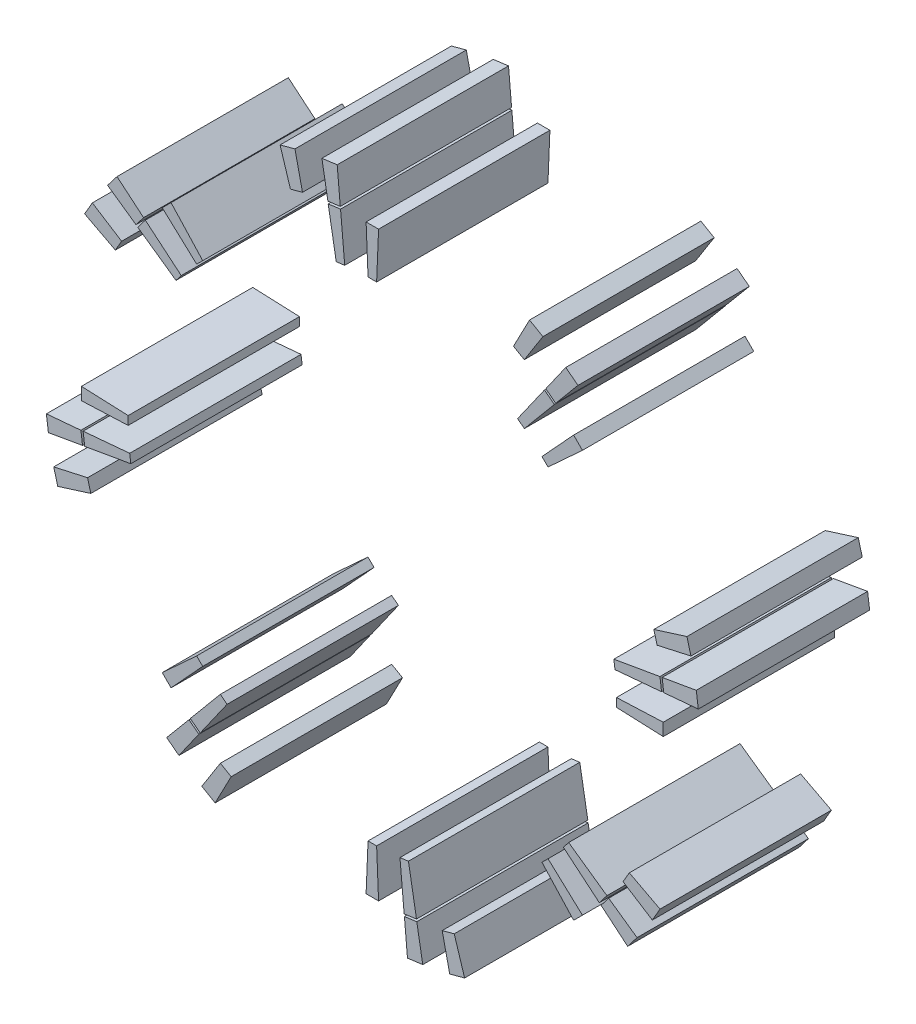
SolidWorks part; units mm, degrees
ref_plane "Спереди" through (0, 0, 0) normal (0, 0, 1) x (1, 0, 0)
ref_plane "Сверху" through (0, 0, 0) normal (0, 1, 0) x (1, 0, 0)
ref_plane "Справа" through (0, 0, 0) normal (1, 0, 0) x (0, 0, -1)
sketch "Эскиз1" plane through (0, 0, 0) normal (0, 0, 1) x (1, 0, 0)
  line L0 (42.755, -0.75) -> (50.9385, -1.0918)
  line L1 (50.9385, -1.0918) -> (50.9385, 1.0918)
  line L2 (50.9385, 1.0918) -> (42.755, 0.75)
  line L3 (42.755, 0.75) -> (42.755, -0.75)
  line L4 (51.0303, 5.617) -> (57.0775, 6.1527)
  line L5 (57.0775, 6.1527) -> (56.7251, 8.8296)
  line L6 (56.7251, 8.8296) -> (50.7452, 7.782)
  line L7 (50.7452, 7.782) -> (51.0303, 5.617)
  line L8 (42.4871, 4.8371) -> (50.6452, 5.5663)
  line L9 (50.6452, 5.5663) -> (50.3602, 7.7313)
  line L10 (50.3602, 7.7313) -> (42.2913, 6.3242)
  line L11 (42.2913, 6.3242) -> (42.4871, 4.8371)
  line L12 (49.8605, 12.2298) -> (55.7861, 13.5502)
  line L13 (55.7861, 13.5502) -> (55.0873, 16.1582)
  line L14 (55.0873, 16.1582) -> (49.2953, 14.339)
  line L15 (49.2953, 14.339) -> (49.8605, 12.2298)
  line L16 (30.7627, 29.702) -> (36.791, 35.2469)
  line L17 (36.791, 35.2469) -> (35.2469, 36.791)
  line L18 (35.2469, 36.791) -> (29.702, 30.7627)
  line L19 (29.702, 30.7627) -> (30.7627, 29.702)
  line L20 (32.112, 40.0557) -> (36.0093, 44.7106)
  line L21 (36.0093, 44.7106) -> (33.8672, 46.3542)
  line L22 (33.8672, 46.3542) -> (30.3796, 41.385)
  line L23 (30.3796, 41.385) -> (32.112, 40.0557)
  line L24 (26.6226, 33.4632) -> (31.8756, 39.7475)
  line L25 (31.8756, 39.7475) -> (30.1432, 41.0769)
  line L26 (30.1432, 41.0769) -> (25.4326, 34.3764)
  line L27 (25.4326, 34.3764) -> (26.6226, 33.4632)
  line L28 (26.609, 43.9044) -> (29.8653, 49.0282)
  line L29 (29.8653, 49.0282) -> (27.527, 50.3782)
  line L30 (27.527, 50.3782) -> (24.7179, 44.9963)
  line L31 (24.7179, 44.9963) -> (26.609, 43.9044)
  line L32 (0.75, 42.755) -> (1.0918, 50.9385)
  line L33 (1.0918, 50.9385) -> (-1.0918, 50.9385)
  line L34 (-1.0918, 50.9385) -> (-0.75, 42.755)
  line L35 (-0.75, 42.755) -> (0.75, 42.755)
  line L36 (-5.617, 51.0303) -> (-6.1527, 57.0775)
  line L37 (-6.1527, 57.0775) -> (-8.8296, 56.7251)
  line L38 (-8.8296, 56.7251) -> (-7.782, 50.7452)
  line L39 (-7.782, 50.7452) -> (-5.617, 51.0303)
  line L40 (-4.8371, 42.4871) -> (-5.5663, 50.6452)
  line L41 (-5.5663, 50.6452) -> (-7.7313, 50.3602)
  line L42 (-7.7313, 50.3602) -> (-6.3242, 42.2913)
  line L43 (-6.3242, 42.2913) -> (-4.8371, 42.4871)
  line L44 (-12.2298, 49.8605) -> (-13.5502, 55.7861)
  line L45 (-13.5502, 55.7861) -> (-16.1582, 55.0873)
  line L46 (-16.1582, 55.0873) -> (-14.339, 49.2953)
  line L47 (-14.339, 49.2953) -> (-12.2298, 49.8605)
  line L48 (-29.702, 30.7627) -> (-35.2469, 36.791)
  line L49 (-35.2469, 36.791) -> (-36.791, 35.2469)
  line L50 (-36.791, 35.2469) -> (-30.7627, 29.702)
  line L51 (-30.7627, 29.702) -> (-29.702, 30.7627)
  line L52 (-40.0557, 32.112) -> (-44.7106, 36.0093)
  line L53 (-44.7106, 36.0093) -> (-46.3542, 33.8672)
  line L54 (-46.3542, 33.8672) -> (-41.385, 30.3796)
  line L55 (-41.385, 30.3796) -> (-40.0557, 32.112)
  line L56 (-33.4632, 26.6226) -> (-39.7475, 31.8756)
  line L57 (-39.7475, 31.8756) -> (-41.0769, 30.1432)
  line L58 (-41.0769, 30.1432) -> (-34.3764, 25.4326)
  line L59 (-34.3764, 25.4326) -> (-33.4632, 26.6226)
  line L60 (-43.9044, 26.609) -> (-49.0282, 29.8653)
  line L61 (-49.0282, 29.8653) -> (-50.3782, 27.527)
  line L62 (-50.3782, 27.527) -> (-44.9963, 24.7179)
  line L63 (-44.9963, 24.7179) -> (-43.9044, 26.609)
  line L64 (-42.755, 0.75) -> (-50.9385, 1.0918)
  line L65 (-50.9385, 1.0918) -> (-50.9385, -1.0918)
  line L66 (-50.9385, -1.0918) -> (-42.755, -0.75)
  line L67 (-42.755, -0.75) -> (-42.755, 0.75)
  line L68 (-51.0303, -5.617) -> (-57.0775, -6.1527)
  line L69 (-57.0775, -6.1527) -> (-56.7251, -8.8296)
  line L70 (-56.7251, -8.8296) -> (-50.7452, -7.782)
  line L71 (-50.7452, -7.782) -> (-51.0303, -5.617)
  line L72 (-42.4871, -4.8371) -> (-50.6452, -5.5663)
  line L73 (-50.6452, -5.5663) -> (-50.3602, -7.7313)
  line L74 (-50.3602, -7.7313) -> (-42.2913, -6.3242)
  line L75 (-42.2913, -6.3242) -> (-42.4871, -4.8371)
  line L76 (-49.8605, -12.2298) -> (-55.7861, -13.5502)
  line L77 (-55.7861, -13.5502) -> (-55.0873, -16.1582)
  line L78 (-55.0873, -16.1582) -> (-49.2953, -14.339)
  line L79 (-49.2953, -14.339) -> (-49.8605, -12.2298)
  line L80 (-30.7627, -29.702) -> (-36.791, -35.2469)
  line L81 (-36.791, -35.2469) -> (-35.2469, -36.791)
  line L82 (-35.2469, -36.791) -> (-29.702, -30.7627)
  line L83 (-29.702, -30.7627) -> (-30.7627, -29.702)
  line L84 (-32.112, -40.0557) -> (-36.0093, -44.7106)
  line L85 (-36.0093, -44.7106) -> (-33.8672, -46.3542)
  line L86 (-33.8672, -46.3542) -> (-30.3796, -41.385)
  line L87 (-30.3796, -41.385) -> (-32.112, -40.0557)
  line L88 (-26.6226, -33.4632) -> (-31.8756, -39.7475)
  line L89 (-31.8756, -39.7475) -> (-30.1432, -41.0769)
  line L90 (-30.1432, -41.0769) -> (-25.4326, -34.3764)
  line L91 (-25.4326, -34.3764) -> (-26.6226, -33.4632)
  line L92 (-26.609, -43.9044) -> (-29.8653, -49.0282)
  line L93 (-29.8653, -49.0282) -> (-27.527, -50.3782)
  line L94 (-27.527, -50.3782) -> (-24.7179, -44.9963)
  line L95 (-24.7179, -44.9963) -> (-26.609, -43.9044)
  line L96 (-0.75, -42.755) -> (-1.0918, -50.9385)
  line L97 (-1.0918, -50.9385) -> (1.0918, -50.9385)
  line L98 (1.0918, -50.9385) -> (0.75, -42.755)
  line L99 (0.75, -42.755) -> (-0.75, -42.755)
  line L100 (5.617, -51.0303) -> (6.1527, -57.0775)
  line L101 (6.1527, -57.0775) -> (8.8296, -56.7251)
  line L102 (8.8296, -56.7251) -> (7.782, -50.7452)
  line L103 (7.782, -50.7452) -> (5.617, -51.0303)
  line L104 (4.8371, -42.4871) -> (5.5663, -50.6452)
  line L105 (5.5663, -50.6452) -> (7.7313, -50.3602)
  line L106 (7.7313, -50.3602) -> (6.3242, -42.2913)
  line L107 (6.3242, -42.2913) -> (4.8371, -42.4871)
  line L108 (12.2298, -49.8605) -> (13.5502, -55.7861)
  line L109 (13.5502, -55.7861) -> (16.1582, -55.0873)
  line L110 (16.1582, -55.0873) -> (14.339, -49.2953)
  line L111 (14.339, -49.2953) -> (12.2298, -49.8605)
  line L112 (29.702, -30.7627) -> (35.2469, -36.791)
  line L113 (35.2469, -36.791) -> (36.791, -35.2469)
  line L114 (36.791, -35.2469) -> (30.7627, -29.702)
  line L115 (30.7627, -29.702) -> (29.702, -30.7627)
  line L116 (40.0557, -32.112) -> (44.7106, -36.0093)
  line L117 (44.7106, -36.0093) -> (46.3542, -33.8672)
  line L118 (46.3542, -33.8672) -> (41.385, -30.3796)
  line L119 (41.385, -30.3796) -> (40.0557, -32.112)
  line L120 (33.4632, -26.6226) -> (39.7475, -31.8756)
  line L121 (39.7475, -31.8756) -> (41.0769, -30.1432)
  line L122 (41.0769, -30.1432) -> (34.3764, -25.4326)
  line L123 (34.3764, -25.4326) -> (33.4632, -26.6226)
  line L124 (43.9044, -26.609) -> (49.0282, -29.8653)
  line L125 (49.0282, -29.8653) -> (50.3782, -27.527)
  line L126 (50.3782, -27.527) -> (44.9963, -24.7179)
  line L127 (44.9963, -24.7179) -> (43.9044, -26.609)
extrude "Slot_copper_envelopes" add sketch "Эскиз1" along normal blind 30 from offset 15 separate body
